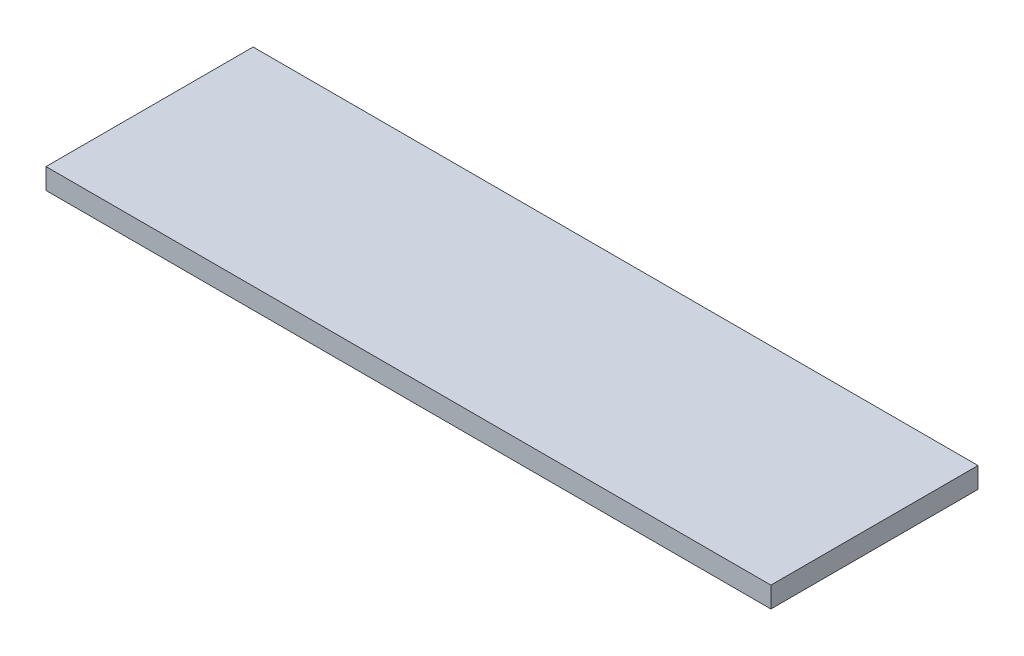
SolidWorks part; units mm, degrees
ref_plane "Front Plane" through (0, 0, 0) normal (0, 0, 1) x (1, 0, 0)
ref_plane "Top Plane" through (0, 0, 0) normal (0, 1, 0) x (1, 0, 0)
ref_plane "Right Plane" through (0, 0, 0) normal (1, 0, 0) x (0, 0, -1)
sketch "Sketch1" plane through (0, 0, 0) normal (0, 1, 0) x (1, 0, 0)
  line L1 (0, 0) -> (70, 0)
  line L2 (0, 0) -> (0, 20)
  line L3 (0, 20) -> (70, 20)
  line L4 (70, 0) -> (70, 20)
  dimension "D1" = 70
  dimension "D2" = 20
extrude "Boss-Extrude1" add sketch "Sketch1" along normal blind 2
